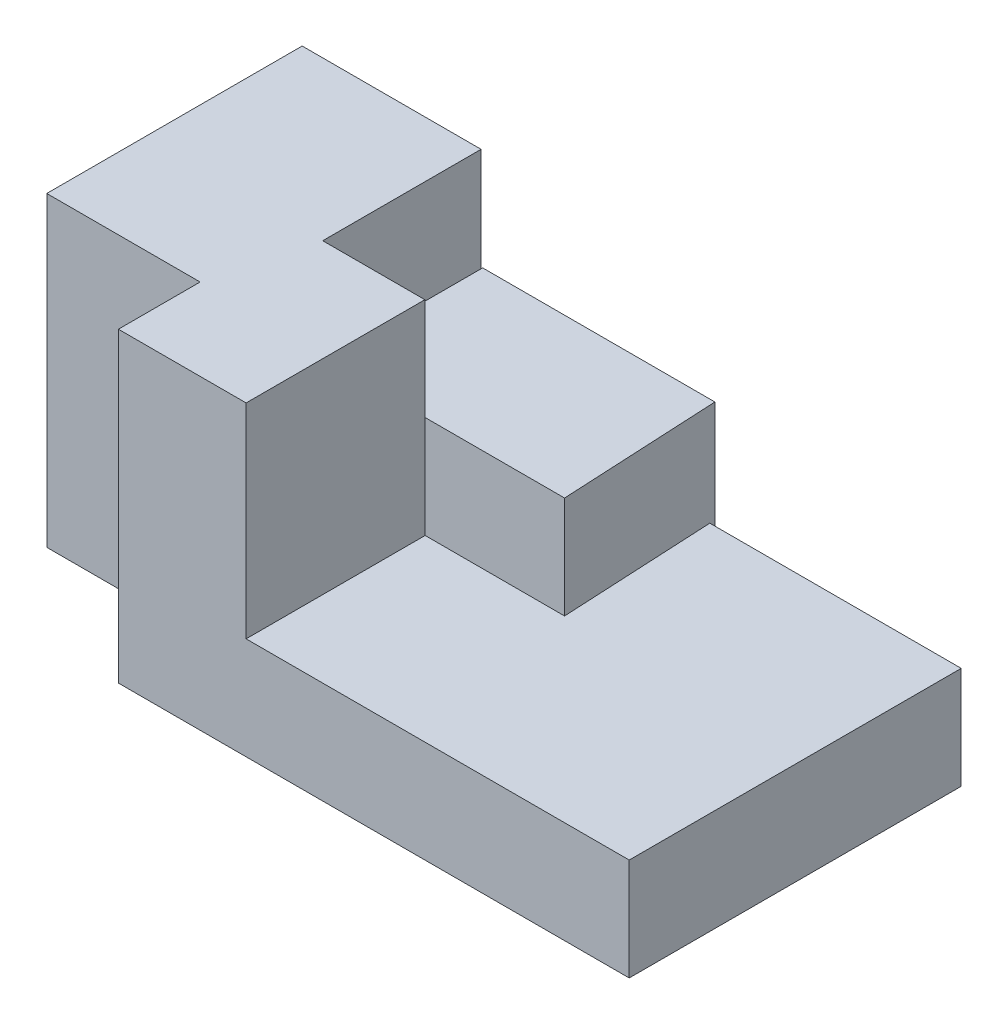
SolidWorks part; units mm, degrees
ref_plane "Front Plane" through (0, 0, 0) normal (0, 0, 1) x (1, 0, 0)
ref_plane "Top Plane" through (0, 0, 0) normal (0, 1, 0) x (1, 0, 0)
ref_plane "Right Plane" through (0, 0, 0) normal (1, 0, 0) x (0, 0, -1)
sketch "Sketch1" plane through (0, 0, 0) normal (0, 1, 0) x (1, 0, 0)
  line L1 (-95.25, -82.55) -> (95.25, -82.55)
  line L2 (-95.25, -82.55) -> (-95.25, 82.55)
  line L3 (-95.25, 82.55) -> (95.25, 82.55)
  line L4 (95.25, -82.55) -> (95.25, 82.55)
  line L5 (-95.25, -82.55) -> (95.25, 82.55) construction
  line L6 (-95.25, 82.55) -> (95.25, -82.55) construction
  point P0 (0, 0)
  dimension "D1" = 165.1
  dimension "D2" = 190.5
extrude "Boss-Extrude1" add sketch "Sketch1" along normal blind 50.8
sketch "Sketch2" plane through (-95.25, 0, 0) normal (-1, 0, 0) x (0, 0, 1)
  line L1 (82.55, 0) -> (-6.35, 0)
  line L2 (82.55, 0) -> (82.55, 152.4)
  line L3 (82.55, 152.4) -> (-6.35, 152.4)
  line L4 (-6.35, 0) -> (-6.35, 152.4)
  dimension "D1" = 152.4
  dimension "D2" = 88.9
extrude "Boss-Extrude2" add sketch "Sketch2" along normal blind 63.5
sketch "Sketch3" plane through (0, 152.4, 0) normal (0, 1, 0) x (1, 0, 0)
  line L0 (-146.05, 6.35) -> (-146.05, 85.09)
  line L1 (-158.75, -82.55) -> (-158.75, 6.35) construction
  line L2 (-158.75, -41.91) -> (-235.0148, -41.91)
  line L3 (-235.0148, -41.91) -> (-235.0148, 85.09)
  line L4 (-235.0148, 85.09) -> (-146.05, 85.09)
  line L7 (-95.25, 6.35) -> (-146.05, 6.35)
  line L8 (-158.75, 6.35) -> (-95.25, 6.35) construction
  line L9 (-146.05, 6.35) -> (-146.05, -41.91)
  line L10 (-146.05, -41.91) -> (-158.75, -41.91)
  line M6 (-95.25, 6.35) -> (-158.75, 6.35)
  line M7 (-158.75, 6.35) -> (-158.75, -82.55)
  dimension "D2" = 127
  dimension "D3" = 50.8
extrude "Boss-Extrude3" add sketch "Sketch3" against normal blind 152.4 contours L4 L3 L2 L0 M7 M6
ref_plane "Plane4" through (0, 101.6, 0) normal (0, 1, 0) x (1, 0, 0)
sketch "Sketch9" plane through (0, 101.6, 0) normal (0, 1, 0) x (1, 0, 0)
  line L0 (-145.3922, 6.4759) -> (-145.3922, 85.217)
  line L1 (-145.3922, 85.217) -> (-29.909, 85.217)
  line L2 (-29.909, 85.217) -> (-25.9205, 6.4759)
  line L3 (-25.9205, 6.4759) -> (-145.3922, 6.4759)
  point P2 (0, 0)
  point P5 (-144.9091, 6.4759)
  point P6 (-145.3922, 85.217)
extrude "Boss-Extrude4" add sketch "Sketch9" against normal blind 93.98
